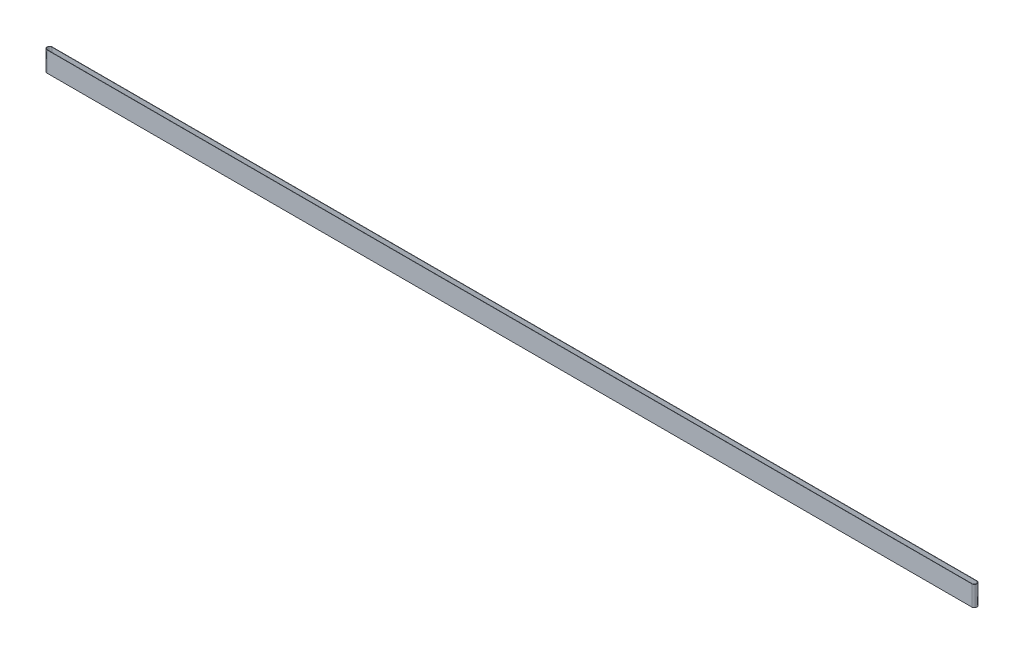
SolidWorks part; units mm, degrees
ref_plane "前视基准面" through (0, 0, 0) normal (0, 0, 1) x (1, 0, 0)
ref_plane "上视基准面" through (0, 0, 0) normal (0, 1, 0) x (1, 0, 0)
ref_plane "右视基准面" through (0, 0, 0) normal (1, 0, 0) x (0, 0, -1)
sketch "草图1" plane through (0, 0, 0) normal (0, 1, 0) x (1, 0, 0)
  line L0 (0, 5) -> (1790, 5)
  line L2 (1790, -5) -> (0, -5)
  line L3 (0, 4.5) -> (1790, 4.5)
  line L5 (1790, -4.5) -> (0, -4.5)
  arc A0 (0, 5) -> (0, -5) centre (0, 0) ccw
  arc A2 (1790, -5) -> (1790, 5) centre (1790, 0) ccw
  arc A3 (0, 4.5) -> (0, -4.5) centre (0, 0) ccw
  arc A4 (1790, -4.5) -> (1790, 4.5) centre (1790, 0) ccw
extrude "凸台-拉伸1" add sketch "草图1" along normal blind 39
